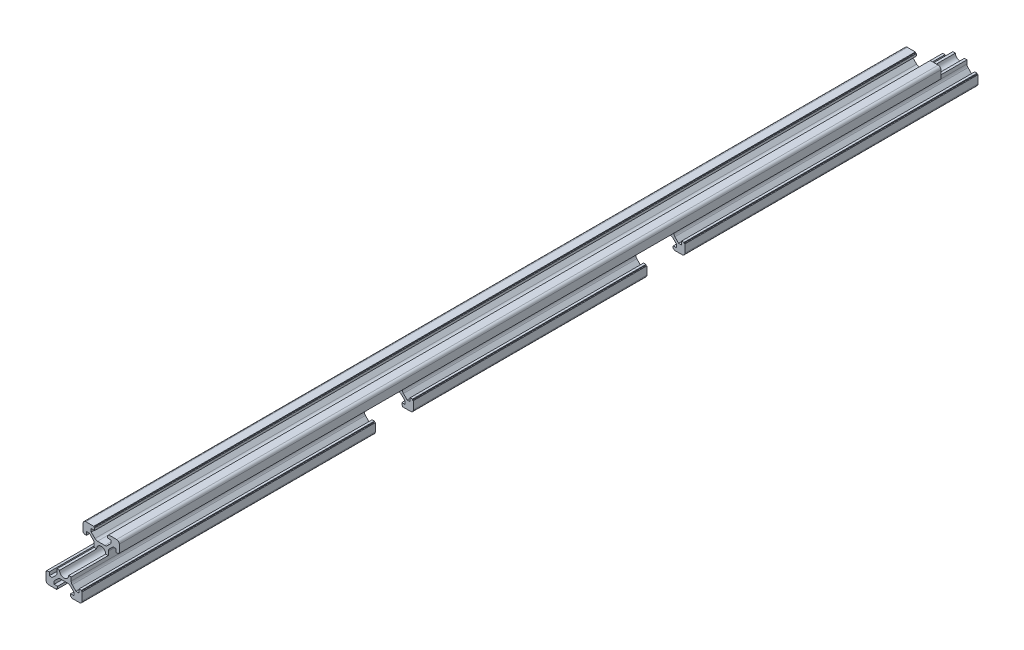
SolidWorks part; units mm, degrees
material "6063-O"
ref_plane "Front Plane" through (0, 0, 0) normal (0, 0, 1) x (1, 0, 0)
ref_plane "Top Plane" through (0, 0, 0) normal (0, 1, 0) x (1, 0, 0)
ref_plane "Right Plane" through (0, 0, 0) normal (1, 0, 0) x (0, 0, -1)
sketch "Sketch1" plane through (0, 0, 0) normal (0, 0, 1) x (1, 0, 0)
  line L0 (10, -4.1) -> (10, -8.5)
  line L1 (4.1, 10) -> (8.5, 10)
  line L2 (8.5, -10) -> (4.1, -10)
  line L3 (-8.5, -10) -> (-4.1, -10)
  line L4 (10, 8.5) -> (10, 4.1)
  line L7 (8.5, 10) -> (4.1, 10)
  line L8 (5.5, 6.5607) -> (3.4251, 4.4858)
  line L9 (8.5, 10) -> (4.1, 10)
  line L10 (3.9, 2.0109) -> (3.9, -2.0109)
  line L11 (2.0109, -3.9) -> (-2.0109, -3.9)
  line L12 (-3.9, -2.0109) -> (-3.9, 2.0109)
  line L13 (-2.0109, 3.9) -> (2.8393, 3.9)
  line L14 (2.5, 0) -> (22.2403, 0) construction
  line L15 (3.6, 9.5) -> (3.6, 8.2)
  line L16 (9.5, 3.6) -> (8.2, 3.6)
  line L17 (8.2, 3.6) -> (8.2, 5.5)
  line L18 (8.2, 5.5) -> (6.5607, 5.5)
  line L19 (10, -4.1) -> (10, -8.5)
  line L20 (4.1, 9.5) -> (3.6, 9.5)
  line L21 (4.1, 10) -> (4.1, 9.5)
  line L22 (8.5, 10) -> (4.1, 10)
  line L23 (10, 4.1) -> (9.5, 4.1)
  line L24 (9.5, 4.1) -> (9.5, 3.6)
  line L25 (5.5, 8.2) -> (5.5, 6.5607)
  line L26 (3.6, 8.2) -> (5.5, 8.2)
  line L27 (4.4858, 3.4251) -> (6.5607, 5.5)
  line L28 (10, -8.5) -> (10, -4.1)
  line L29 (6.5607, -5.5) -> (4.4858, -3.4251)
  line L30 (10, -8.5) -> (10, -4.1)
  line L31 (2.0109, -3.9) -> (-2.0109, -3.9)
  line L32 (3.9, 2.8393) -> (3.9, -2.0109)
  line L33 (9.5, -3.6) -> (8.2, -3.6)
  line L34 (3.6, -9.5) -> (3.6, -8.2)
  line L35 (3.6, -8.2) -> (5.5, -8.2)
  line L36 (5.5, -8.2) -> (5.5, -6.5607)
  line L37 (9.5, -4.1) -> (9.5, -3.6)
  line L38 (10, -4.1) -> (9.5, -4.1)
  line L39 (10, -8.5) -> (10, -4.1)
  line L40 (4.1, -10) -> (4.1, -9.5)
  line L41 (4.1, -9.5) -> (3.6, -9.5)
  line L42 (8.2, -5.5) -> (6.5607, -5.5)
  line L43 (8.2, -3.6) -> (8.2, -5.5)
  line L44 (3.4251, -4.4858) -> (5.5, -6.5607)
  line L45 (-4.1, -10) -> (-8.5, -10)
  line L46 (-10, -8.5) -> (-10, -4.1)
  line L47 (-8.5, -10) -> (-4.1, -10)
  line L48 (-5.5, -6.5607) -> (-3.4251, -4.4858)
  line L49 (-8.5, -10) -> (-4.1, -10)
  line L50 (-3.9, -2.0109) -> (-3.9, 2.0109)
  line L51 (2.0109, -3.9) -> (-2.0109, -3.9)
  line L52 (-3.6, -9.5) -> (-3.6, -8.2)
  line L53 (-9.5, -3.6) -> (-8.2, -3.6)
  line L54 (-8.2, -3.6) -> (-8.2, -5.5)
  line L55 (-8.2, -5.5) -> (-6.5607, -5.5)
  line L56 (-4.1, -9.5) -> (-3.6, -9.5)
  line L57 (-4.1, -10) -> (-4.1, -9.5)
  line L58 (-8.5, -10) -> (-4.1, -10)
  line L59 (-10, -4.1) -> (-9.5, -4.1)
  line L60 (-9.5, -4.1) -> (-9.5, -3.6)
  line L61 (-5.5, -8.2) -> (-5.5, -6.5607)
  line L62 (-3.6, -8.2) -> (-5.5, -8.2)
  line L63 (-4.4858, -3.4251) -> (-6.5607, -5.5)
  line L64 (-10, 4.1) -> (-10, 8.5)
  line L65 (-8.5, 10) -> (-4.1, 10)
  line L66 (-10, 8.5) -> (-10, 4.1)
  line L67 (-6.5607, 5.5) -> (-4.4858, 3.4251)
  line L68 (-10, 8.5) -> (-10, 4.1)
  line L69 (-2.0109, 3.9) -> (2.0109, 3.9)
  line L70 (-3.9, -2.0109) -> (-3.9, 2.0109)
  line L71 (-9.5, 3.6) -> (-8.2, 3.6)
  line L72 (-3.6, 9.5) -> (-3.6, 8.2)
  line L73 (-3.6, 8.2) -> (-5.5, 8.2)
  line L74 (-5.5, 8.2) -> (-5.5, 6.5607)
  line L75 (-9.5, 4.1) -> (-9.5, 3.6)
  line L76 (-10, 4.1) -> (-9.5, 4.1)
  line L77 (-10, 8.5) -> (-10, 4.1)
  line L78 (-4.1, 10) -> (-4.1, 9.5)
  line L79 (-4.1, 9.5) -> (-3.6, 9.5)
  line L80 (-8.2, 5.5) -> (-6.5607, 5.5)
  line L81 (-8.2, 3.6) -> (-8.2, 5.5)
  line L82 (-3.4251, 4.4858) -> (-5.5, 6.5607)
  line L83 (4.1, -10) -> (8.5, -10)
  arc A0 (2.0109, -3.9) -> (3.4251, -4.4858) centre (2.0109, -5.9) cw
  arc A1 (4.4858, -3.4251) -> (3.9, -2.0109) centre (5.9, -2.0109) cw
  arc A2 (3.9, 2.0109) -> (4.4858, 3.4251) centre (5.9, 2.0109) cw
  arc A3 (2.0109, 3.9) -> (3.4251, 4.4858) centre (2.0109, 5.9) ccw
  arc A4 (-2.0109, 3.9) -> (-3.4251, 4.4858) centre (-2.0109, 5.9) cw
  arc A5 (-4.4858, 3.4251) -> (-3.9, 2.0109) centre (-5.9, 2.0109) cw
  arc A6 (-3.4251, -4.4858) -> (-2.0109, -3.9) centre (-2.0109, -5.9) cw
  arc A7 (-3.9, -2.0109) -> (-4.4858, -3.4251) centre (-5.9, -2.0109) cw
  circle A8 centre (0, 0) radius 2.5
  arc A9 (-8.5, -10) -> (-10, -8.5) centre (-8.5, -8.5) cw
  arc A10 (-10, 8.5) -> (-8.5, 10) centre (-8.5, 8.5) cw
  arc A11 (8.5, 10) -> (10, 8.5) centre (8.5, 8.5) cw
  arc A12 (8.5, -10) -> (10, -8.5) centre (8.5, -8.5) ccw
  point P0 (0, 0)
  point P86 (0, 0)
  point P107 (10, -10)
  dimension "D3" = 2
  dimension "D5" = 5
  dimension "D2" = 1.5
  dimension "D8" = 1.5
  dimension "D6" = 4
  dimension "D7" = 6.1
  dimension "D11" = 0.5
  dimension "D12" = 0.5
extrude "Boss-Extrude2" add sketch "Sketch1" along normal blind 495
sketch "ｽｹｯﾁ1" plane through (-10, 0, 0) normal (-1, 0, 0) x (0, 0, 1)
  line L0 (495, 10) -> (0, 10) construction
  line L10 (247.5, 10) -> (247.5, -66.4608) construction
  line L20 (183, 0) -> (162, 0)
  line L21 (183, 0) -> (183, -10)
  line L22 (183, -10) -> (162, -10)
  line L23 (162, 0) -> (162, -10)
  line L24 (0, 0) -> (20.5, 0)
  line L25 (0, 0) -> (0, 10)
  line L26 (0, 10) -> (20.5, 10)
  line L27 (20.5, 0) -> (20.5, 10)
  line L34 (474.5, 0) -> (495, 0)
  line L52 (474.5, 0) -> (474.5, 10)
  line L53 (474.5, 10) -> (495, 10)
  line L54 (495, 0) -> (495, 10)
  line L55 (495, -10) -> (0, -10) construction
  line L56 (312, -10) -> (333, -10)
  line L57 (312, -10) -> (312, 0)
  line L58 (312, 0) -> (333, 0)
  line L59 (333, -10) -> (333, 0)
  dimension "D1" = 64.5
  dimension "D2" = 21
  dimension "D3" = 64.5
  dimension "D4" = 21
extrude "ｶｯﾄ - 押し出し1" cut sketch "ｽｹｯﾁ1" against normal through all
